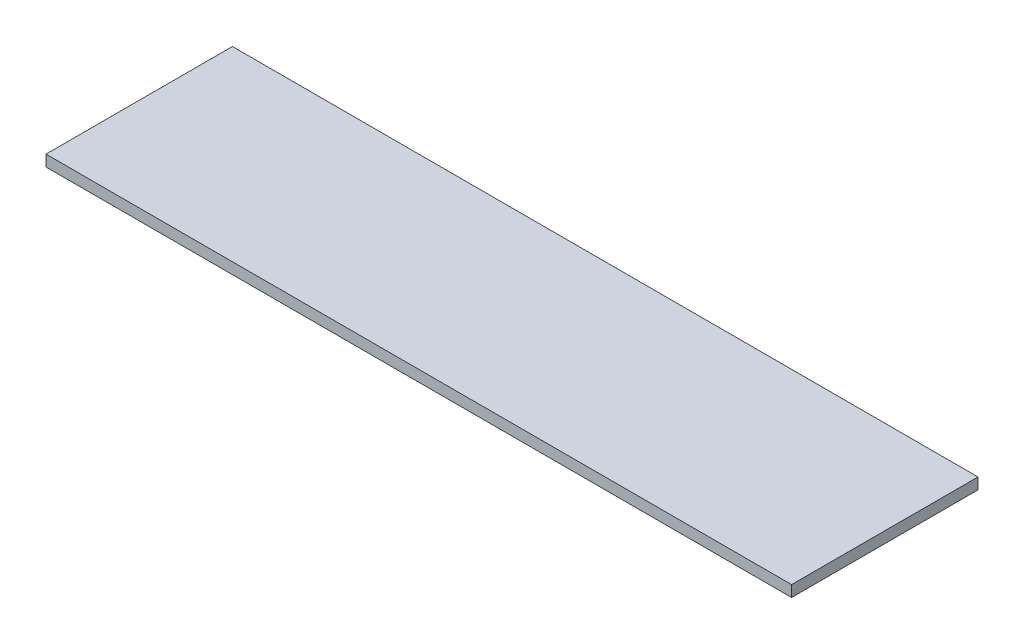
SolidWorks part; units mm, degrees
ref_plane "前视基准面" through (0, 0, 0) normal (0, 0, 1) x (1, 0, 0)
ref_plane "上视基准面" through (0, 0, 0) normal (0, 1, 0) x (1, 0, 0)
ref_plane "右视基准面" through (0, 0, 0) normal (1, 0, 0) x (0, 0, -1)
sketch "草图1" plane through (0, 0, 0) normal (0, 1, 0) x (1, 0, 0)
  line L1 (-100, 25) -> (100, 25)
  line L2 (-100, 25) -> (-100, -25)
  line L3 (-100, -25) -> (100, -25)
  line L4 (100, 25) -> (100, -25)
  line L5 (-100, 25) -> (100, -25) construction
  line L6 (-100, -25) -> (100, 25) construction
  point P0 (0, 0)
  dimension "D1" = 50
  dimension "D2" = 200
extrude "凸台-拉伸1" add sketch "草图1" along normal blind 3
